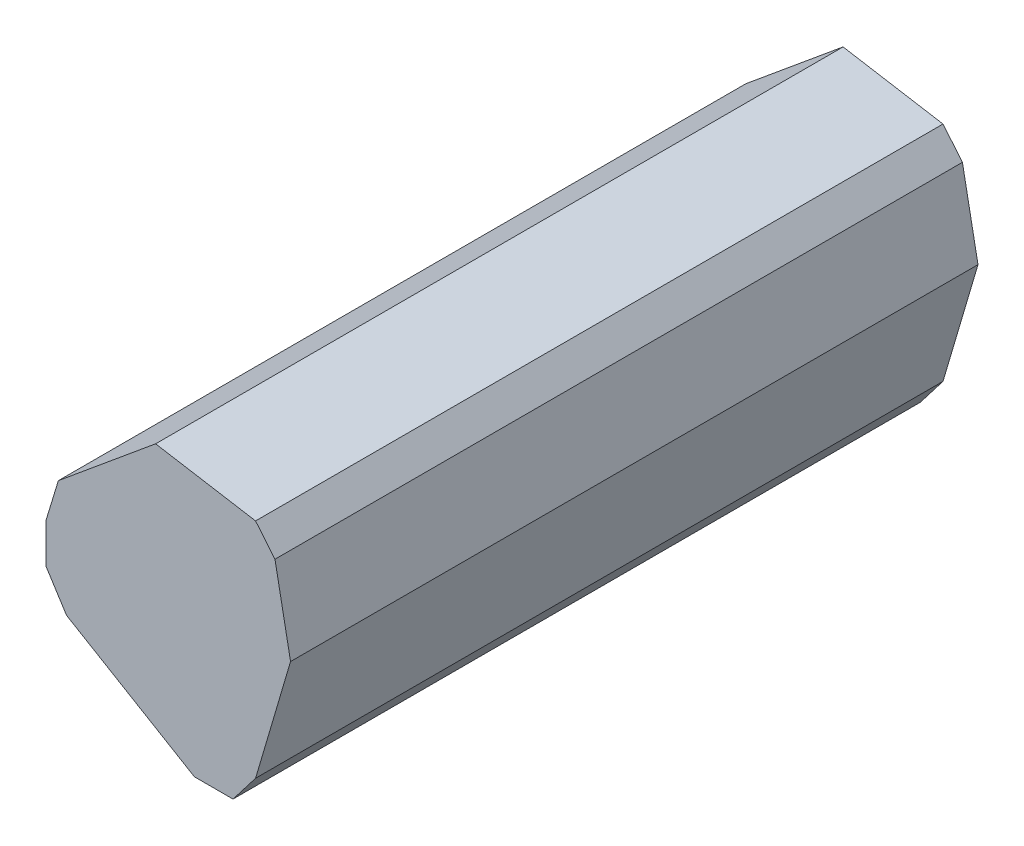
SolidWorks part; units mm, degrees
ref_plane "Plan de face" through (0, 0, 0) normal (0, 0, 1) x (1, 0, 0)
ref_plane "Plan de dessus" through (0, 0, 0) normal (0, 1, 0) x (1, 0, 0)
ref_plane "Plan de droite" through (0, 0, 0) normal (1, 0, 0) x (0, 0, -1)
sketch "Esquisse1" plane through (0, 0, 0) normal (0, 0, 1) x (1, 0, 0)
  line L8 (0, -6.8229) -> (4.2441, -3.3093)
  line L9 (4.2441, -3.3093) -> (8.6057, -4.0426)
  line L10 (8.6057, -4.0426) -> (9.453, -5.0661)
  line L11 (9.453, -5.0661) -> (10.1324, -8.5946)
  line L12 (10.1324, -8.5946) -> (8.6057, -13.7685)
  line L13 (8.6057, -13.7685) -> (7.6223, -15.0474)
  line L14 (7.6223, -15.0474) -> (5.937, -15.0474)
  line L15 (5.937, -15.0474) -> (0.3557, -11.7351)
  line L16 (0.3557, -11.7351) -> (-0.5396, -10.3301)
  line L17 (-0.5396, -10.3301) -> (-0.5396, -8.5946)
  line L18 (-0.5396, -8.5946) -> (0, -6.8229)
  circle A0 centre (5.937, -9.3484) radius 7.5 construction
  dimension "D1" = 15
extrude "Boss.-Extru.1" add sketch "Esquisse1" along normal blind 30
sketch "Esquisse7" plane through (-0.4244, -2.5244, 0) normal (0.1658, 0.9862, 0) x (0.9862, -0.1658, 0)
  line L0 (8.0958, -33.6153) -> (-1.8806, -17.726) construction
